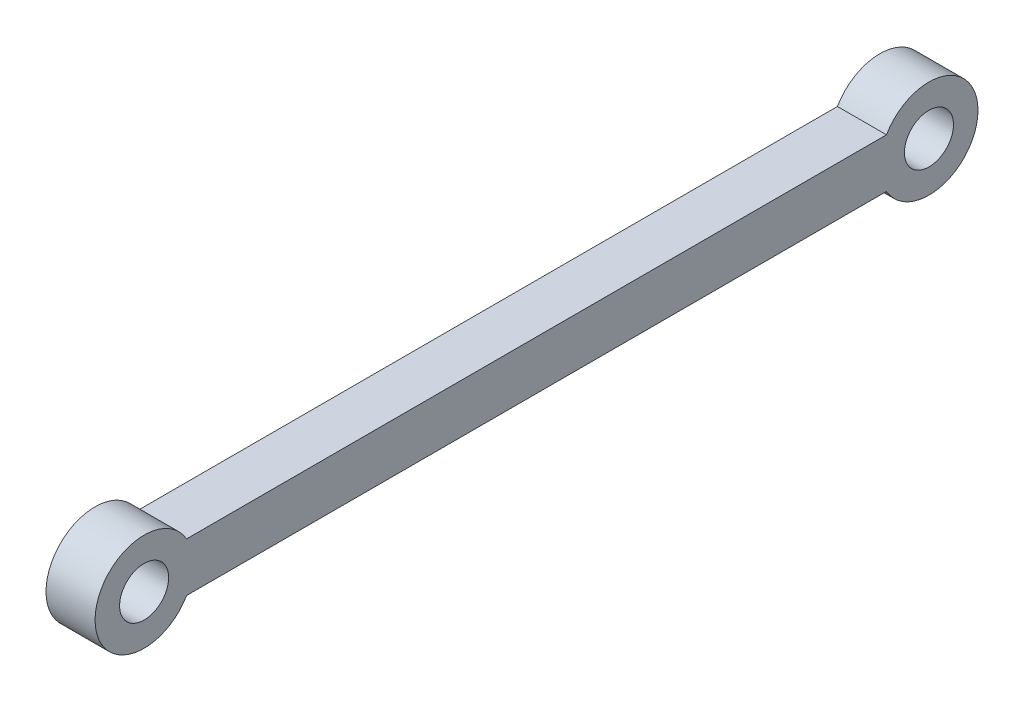
SolidWorks part; units mm, degrees
ref_plane "정면" through (0, 0, 0) normal (0, 0, 1) x (1, 0, 0)
ref_plane "윗면" through (0, 0, 0) normal (0, 1, 0) x (1, 0, 0)
ref_plane "우측면" through (0, 0, 0) normal (1, 0, 0) x (0, 0, -1)
sketch "스케치1" plane through (0, 0, 0) normal (1, 0, 0) x (0, 0, -1)
  line L0 (-20, 0) -> (20, 0) construction
  line L1 (-17.8349, 1.25) -> (17.8349, 1.25)
  line L3 (-17.8349, -1.25) -> (17.8349, -1.25)
  line L5 (0, 1.25) -> (0, -1.25) construction
  arc A0 (-17.8349, 1.25) -> (-17.8349, -1.25) centre (-20, 0) ccw
  circle A1 centre (-20, 0) radius 1.25
  arc A2 (17.8349, -1.25) -> (17.8349, 1.25) centre (20, 0) ccw
  circle A3 centre (20, 0) radius 1.25
  dimension "D3" = 5
  dimension "D4" = 5
  dimension "D1" = 2.5
  dimension "D2" = 40
extrude "보스-돌출1" add sketch "스케치1" along normal blind 2.5
equation "\"link11\" = 80"
equation "\"link12\" = 40"
equation "\"link21\"= 60"
equation "\"link22\"= 40"
equation "\"link31\"= 50"
equation "\"link32\"= 40"
equation "\"link41\"= 40"
equation "\"link42\"= 40"
equation "\"D2@스케치1\"=\"link22\""
